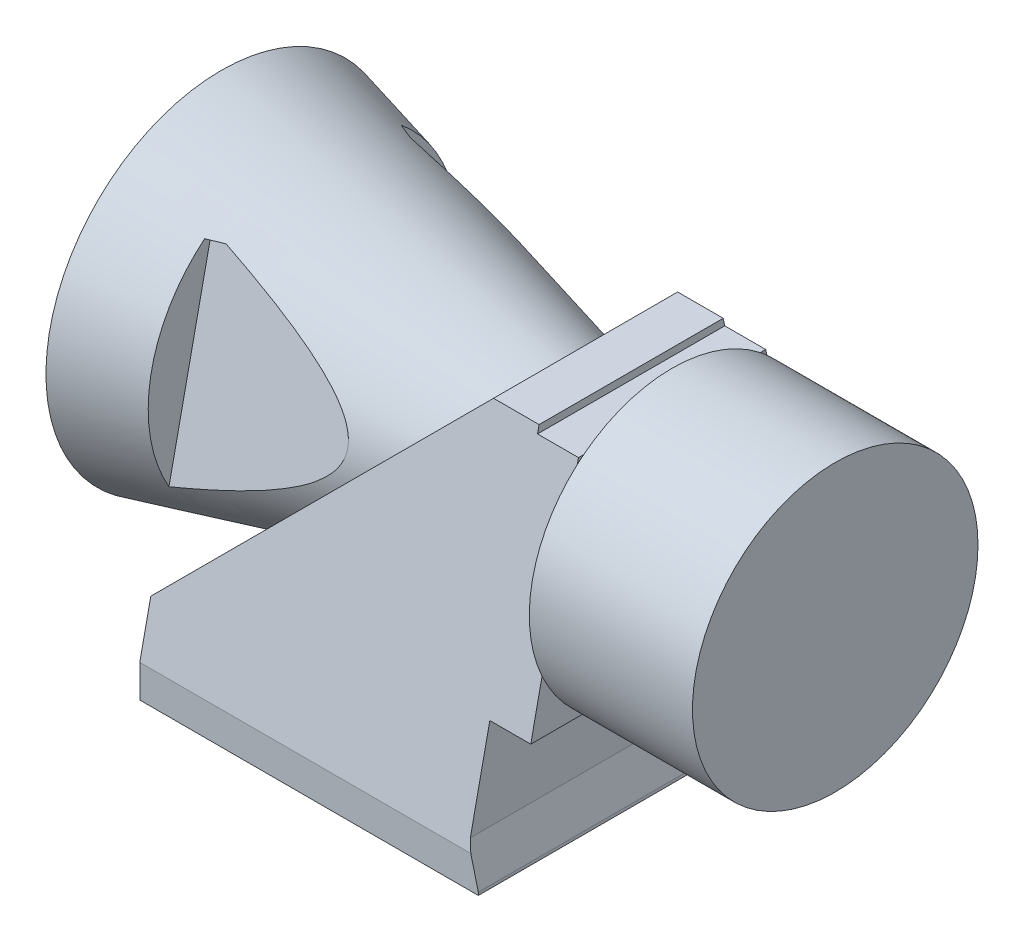
SolidWorks part; units mm, degrees
ref_plane "前视基准面" through (0, 0, 0) normal (0, 0, 1) x (1, 0, 0)
ref_plane "上视基准面" through (0, 0, 0) normal (0, 1, 0) x (1, 0, 0)
ref_plane "右视基准面" through (0, 0, 0) normal (1, 0, 0) x (0, 0, -1)
sketch "草图1" plane through (0, 0, 0) normal (0, 0, 1) x (1, 0, 0)
  line L0 (0, 0) -> (0, 20)
  line L1 (0, 0) -> (83, 0) construction
  line L2 (80.4667, 60) -> (40, 60) construction
  line L3 (69.3, 89.3) -> (80.4667, 89.3)
  line L4 (80.4667, 89.3) -> (80.4667, 87.5)
  line L5 (80.4667, 10) -> (83, 0)
  line L6 (0, -0.7) -> (83, -0.7)
  line L7 (83, 0) -> (83, -0.7)
  line L8 (0, 0) -> (0, -0.7)
  line L9 (40, 60) -> (40, -0.7) construction
  line L10 (0, 20) -> (69.3, 89.3)
  line L11 (0, 20) -> (-20, 20) construction
  line L12 (-20, 20) -> (-20, 103) construction
  line L13 (-20, 103) -> (80.4667, 87.5) construction
  line L14 (80.4667, 32.5) -> (-20, 20) construction
  line L15 (80.4667, 87.5) -> (90.5, 87.5)
  line L16 (90.5, 87.5) -> (90.5, 32.5)
  line L17 (90.5, 32.5) -> (80.4667, 32.5)
  line L18 (80.4667, 32.5) -> (80.4667, 10)
  line L19 (80.4667, 87.5) -> (80.4667, 32.5) construction
  line L20 (80.4667, 89.3) -> (80.4667, 32.5) construction
  line L21 (80.4667, 60) -> (92.5, 60) construction
  line L22 (92.5, 74.5) -> (92.5, 45.5) construction
  line L23 (92.5, 74.5) -> (-20, 103) construction
  line L24 (-20, 20) -> (92.5, 45.5) construction
  point P9 (80.4667, 32.5)
  point P16 (69.2331, 89.2331)
  point P18 (80.4667, 87.5)
  point P19 (2.842, 22.842)
  point P29 (62.1809, 82.1809)
  dimension "D1" = 45
  dimension "D2" = 0.7
  dimension "D3" = 83
  dimension "D4" = 10
  dimension "D5" = 60
  dimension "D6" = 55
  dimension "D7" = 93.8912
  dimension "D8" = 20
  dimension "D9" = 2
  dimension "D10" = 40.4667
  dimension "D11" = 60.7
  dimension "D12" = 52.5
  dimension "D13" = 29
  dimension "D14" = 90
  dimension "D15" = 112.5
extrude "凸台-拉伸1" add sketch "草图1" along normal blind 80
sketch "草图2" plane through (90.5, 0, 0) normal (1, 0, 0) x (0, 0, -1)
  line L0 (-80, 60) -> (0, 60) construction
  line L1 (-80, 32.5) -> (-80, 87.5) construction
  line L2 (0, 32.5) -> (0, 87.5) construction
  line L3 (-40, 89.3) -> (-40, -0.7) construction
  line L4 (-80, 89.3) -> (0, 89.3) construction
  line L5 (-80, -0.7) -> (0, -0.7) construction
  circle A0 centre (-40, 60) radius 35
  dimension "D1" = 70
extrude "凸台-拉伸2" add sketch "草图2" along normal blind 40
ref_plane "基准面5" through (0, 0, 40) normal (0, 0, -1) x (-1, 0, 0)
sketch "草图3" plane through (0, 0, 40) normal (0, 0, 1) x (1, 0, 0)
  line L0 (92.5, 60) -> (40, 60) construction
  line L1 (92.5, 60) -> (92.5, 74.5)
  line L2 (92.5, 74.5) -> (-20, 103)
  line L3 (-20, 103) -> (-20, 60)
  line L4 (-20, 20) -> (-20, 103) construction
  line L5 (-20, 60) -> (92.5, 60)
revolve "旋转1" add sketch "草图3" angle 360 about L0
sketch "草图4" plane through (-10, 10, 0) normal (-0.7071, 0.7071, 0) x (0, 0, 1)
  spline S0 degree 3 poles (40, 18.0565) (97.4749, 18.0565) (97.4749, 102.0791) (40, 102.0791) (-17.4749, 102.0791) (-17.4749, 18.0565) (40, 18.0565) (97.4749, 18.0565) (97.4749, 102.0791) knots -0.5 0 0 0 0.5 0.5 0.5 1 1 1 1.5 1.5 1.5 weights 1 0.333333 0.333333 1 0.333333 0.333333 1 0.333333 0.333333 only from (40, 18.0565) to (40, 18.0565)
  spline S1 degree 3 poles (40, 18.0565) (97.4749, 18.0565) (97.4749, 102.0791) (40, 102.0791) (-17.4749, 102.0791) (-17.4749, 18.0565) (40, 18.0565) (97.4749, 18.0565) (97.4749, 102.0791) knots -0.5 0 0 0 0.5 0.5 0.5 1 1 1 1.5 1.5 1.5 weights 1 0.333333 0.333333 1 0.333333 0.333333 1 0.333333 0.333333 only from (40, 18.0565) to (40, 18.0565) construction
sketch "草图5" plane through (0, 0, 0) normal (-1, 0, 0) x (0, 0, 1)
  line L0 (0, 7.3) -> (17.4296, 89.3)
  line L1 (80, 89.3) -> (0, 89.3) construction
  line L2 (17.4296, 89.3) -> (62.5704, 89.3)
  line L3 (62.5704, 89.3) -> (80, 7.3)
  line L4 (80, 20) -> (0, 20) construction
  line L5 (17.4296, 89.3) -> (0, 89.3)
  line L6 (0, 89.3) -> (0, 7.3)
  line L7 (62.5704, 89.3) -> (80, 89.3)
  line L8 (80, 89.3) -> (80, 7.3)
  line L9 (0, 60) -> (0, -0.7) construction
  line L10 (80, 20) -> (80, -0.7) construction
  line L11 (80, -0.7) -> (0, -0.7) construction
  dimension "D1" = 78
  dimension "D2" = 78
  dimension "D3" = 8
extrude "切除-拉伸1" cut sketch "草图5" against normal up to surface (90.5 mm away) contours L5 L6 L0 | L7 L8 L3
